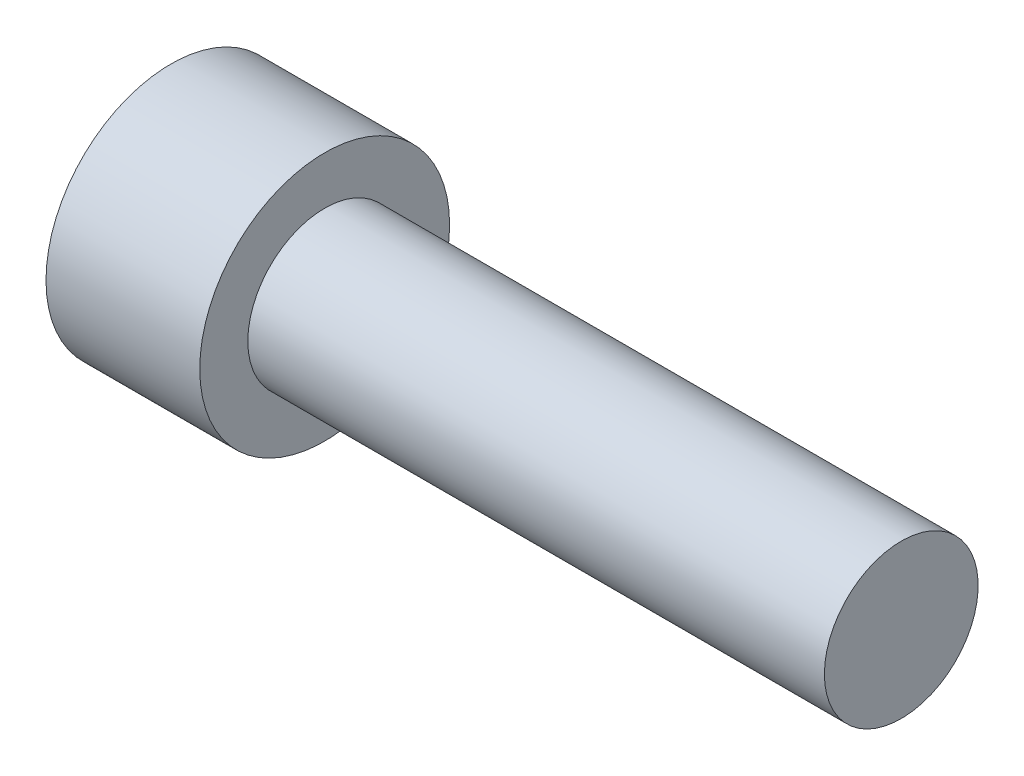
SolidWorks part; units mm, degrees
ref_plane "Front Plane" through (0, 0, 0) normal (0, 0, 1) x (1, 0, 0)
ref_plane "Top Plane" through (0, 0, 0) normal (0, 1, 0) x (1, 0, 0)
ref_plane "Right Plane" through (0, 0, 0) normal (1, 0, 0) x (0, 0, -1)
sketch "Sketch1" plane through (0, 0, 0) normal (0, 0, 1) x (1, 0, 0)
  line L0 (0, 0) -> (38, 0) construction
  line L3 (0, 0) -> (0, 6.5)
  line L4 (0, 6.5) -> (8, 6.5)
  line L5 (8, 4) -> (8, 6.5)
  line L6 (8, 4) -> (38, 4)
  line L8 (0, 0) -> (38, 0)
  line L9 (38, 4) -> (38, 0)
  dimension "CS_A" = 13
  dimension "CS_E" = 8
  dimension "CS_L" = 30
  dimension "CS_M" = 8
revolve "Revolve1" add sketch "Sketch1" angle 360 about L0
cosmetic thread "Cosmetic Thread1" parameters "CS_D_s"=6.891
sketch "Sketch2" plane through (0, 0, 0) normal (0, 0, 1) x (1, 0, 0)
  line L0 (0, 0) -> (38, 0) construction
  line L1 (0, 6.5) -> (0, -6.5) construction
  line L2 (38, -4) -> (38, 4) construction
  line L3 (0, 3) -> (4, 3)
  line L4 (4, 3) -> (5.7321, 0)
  line L5 (0, 3) -> (0, 0)
  line L6 (0, 0) -> (5.7321, 0)
  dimension "D1" = 60
  dimension "CS_T_s" = 4
  dimension "CS_B" = 6
revolve "Cut-Revolve1" cut sketch "Sketch2" angle 360 about L0
sketch "Sketch3" plane through (0, 0, 0) normal (-1, 0, 0) x (0, 0, 1)
  line L0 (0, 0) -> (0, 6.5) construction
  line L1 (0, -3.4641) -> (3, -1.7321)
  line L2 (3, -1.7321) -> (3, 1.7321)
  line L3 (3, 1.7321) -> (0, 3.4641)
  line L4 (0, 3.4641) -> (-3, 1.7321)
  line L5 (-3, 1.7321) -> (-3, -1.7321)
  line L6 (-3, -1.7321) -> (0, -3.4641)
  circle A0 centre (0, 0) radius 3 construction
  circle A1 centre (0, 0) radius 6.5 construction
  circle A2 centre (0, 0) radius 3 construction
extrude "Cut-Extrude1" cut sketch "Sketch3" against normal blind 4
